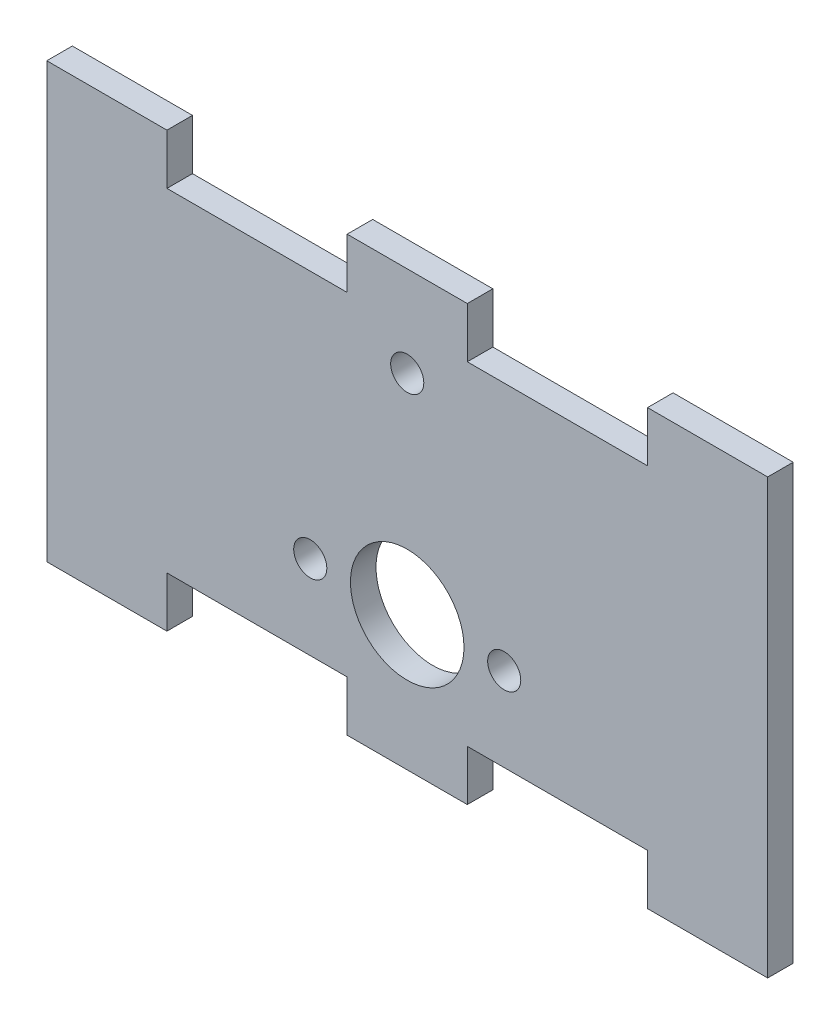
SolidWorks part; units mm, degrees
ref_plane "Front Plane" through (0, 0, 0) normal (0, 0, 1) x (1, 0, 0)
ref_plane "Top Plane" through (0, 0, 0) normal (0, 1, 0) x (1, 0, 0)
ref_plane "Right Plane" through (0, 0, 0) normal (1, 0, 0) x (0, 0, -1)
sketch "Sketch1" plane through (0, 0, 0) normal (0, 0, 1) x (1, 0, 0)
  line L1 (-38.1, 17.6) -> (38.1, 17.6)
  line L2 (-38.1, 17.6) -> (-38.1, -17.6)
  line L3 (-38.1, -17.6) -> (38.1, -17.6)
  line L4 (38.1, 17.6) -> (38.1, -17.6)
  line L5 (-38.1, 17.6) -> (38.1, -17.6) construction
  line L6 (-38.1, -17.6) -> (38.1, 17.6) construction
  point P0 (0, 0)
  dimension "D1" = 76.2
  dimension "D2" = 35.2
extrude "Base Shape" add sketch "Sketch1" against normal blind 2.7
sketch "Sketch2" plane through (0, 0, 0) normal (0, 0, 1) x (1, 0, 0)
  line L0 (0, 24.1745) -> (0, -22.4233) construction
  line L1 (-43.8567, 0) -> (43.7806, 0) construction
  line L2 (-45.3034, 0) -> (-45.3034, -8.73) construction
  line L3 (0, -24.9359) -> (10.25, -24.9359) construction
  line L4 (0, -24.9359) -> (-10.25, -24.9359) construction
  line L5 (43.0953, -8.73) -> (43.0953, 13.37) construction
  circle A0 centre (0, -8.73) radius 6
  circle A1 centre (-10.25, -8.73) radius 1.75
  circle A2 centre (10.25, -8.73) radius 1.75
  circle A3 centre (0, 13.37) radius 1.75
  dimension "D2" = 12
  dimension "D5" = 3.5
  dimension "D6" = 3.5
  dimension "D8" = 3.5
  dimension "D1" = 8.73
  dimension "D3" = 10.25
  dimension "D4" = 10.25
  dimension "D7" = 22.1
extrude "Motor Holes" cut sketch "Sketch2" against normal through all
sketch "Sketch3" plane through (0, 17.6, 0) normal (0, 1, 0) x (1, 0, 0)
  line L0 (-38.1, 5.5354) -> (-25.4, 5.5354) construction
  line L1 (0, 17.1004) -> (0, 2.7) construction
  line L2 (0, 6.041) -> (-6.35, 6.041) construction
  line L3 (38.1, 0) -> (-38.1, 0) construction
  line L4 (-38.1, 2.7) -> (-25.4, 2.7)
  line L5 (-38.1, 2.7) -> (-38.1, 0)
  line L6 (-38.1, 0) -> (-25.4, 0)
  line L7 (-25.4, 2.7) -> (-25.4, 0)
  line L8 (38.1, 2.7) -> (-38.1, 2.7) construction
  line L9 (-6.35, 2.7) -> (6.35, 2.7)
  line L10 (-6.35, 2.7) -> (-6.35, 0)
  line L11 (-6.35, 0) -> (6.35, 0)
  line L12 (6.35, 2.7) -> (6.35, 0)
  line L13 (0, 0) -> (0, -6.5351) construction
  line L14 (25.4, 2.7) -> (25.4, 0)
  line L15 (38.1, 0) -> (25.4, 0)
  line L16 (38.1, 2.7) -> (38.1, 0)
  line L17 (38.1, 2.7) -> (25.4, 2.7)
  dimension "D1" = 12.7
  dimension "D2" = 6.35
extrude "Top teeth" add sketch "Sketch3" along normal blind 5.334
sketch "Sketch4" plane through (0, -17.6, 0) normal (0, -1, 0) x (1, 0, 0)
  line L0 (0, 3.8282) -> (0, 0) construction
  line L1 (-38.1, -2.7) -> (38.1, -2.7) construction
  line L2 (-38.1, 0) -> (-25.4, 0)
  line L3 (-38.1, 0) -> (-38.1, -2.7)
  line L4 (-38.1, -2.7) -> (-25.4, -2.7)
  line L5 (-25.4, 0) -> (-25.4, -2.7)
  line L6 (-38.1, 0) -> (38.1, 0) construction
  line L7 (0, -2.7) -> (0, -8.1835) construction
  line L8 (6.35, -2.7) -> (6.35, 0)
  line L9 (25.4, 0) -> (25.4, -2.7)
  line L10 (38.1, -2.7) -> (25.4, -2.7)
  line L11 (6.35, -2.7) -> (-6.35, -2.7)
  line L12 (38.1, 0) -> (38.1, -2.7)
  line L13 (6.35, 0) -> (-6.35, 0)
  line L14 (-6.35, -2.7) -> (-6.35, 0)
  line L15 (38.1, 0) -> (25.4, 0)
  dimension "D1" = 12.7
  dimension "D2" = 6.35
extrude "Bottom teeth" add sketch "Sketch4" along normal blind 5.334
sketch "SideSlots" plane through (0, 0, 0) normal (0, 0, 1) x (1, 0, 0)
  line L0 (-44.542, -17.6) -> (44.6943, -17.6) construction
  line L1 (-25.4, 26.8394) -> (-25.4, -28.8952) construction
  line L2 (0, 26.8394) -> (0, -28.8952) construction
  line L3 (41.6487, 0) -> (-44.542, 0) construction
  circle A0 centre (0, 0) radius 17.6 construction
  dimension "D1" = 35.2
